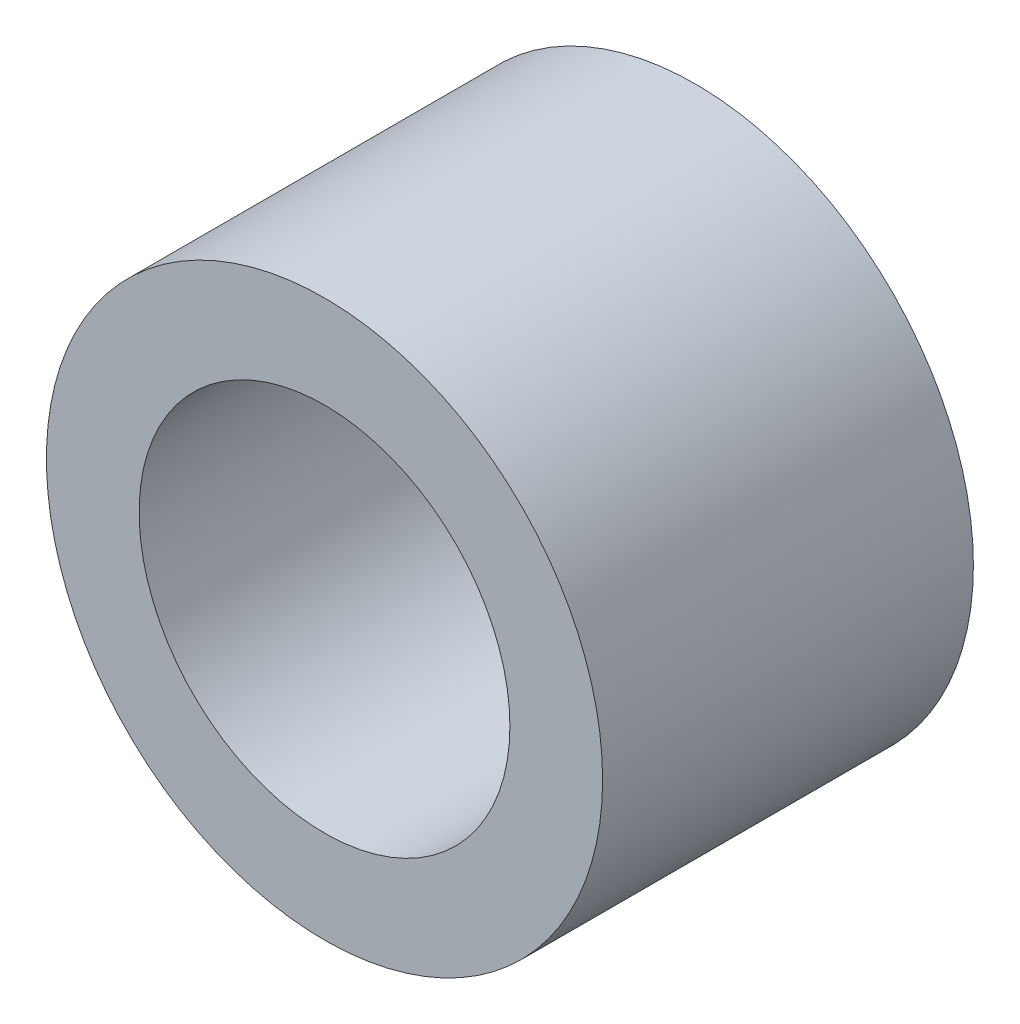
SolidWorks part; units mm, degrees
material "Tin Bearing Bronze"
ref_plane "Front" through (0, 0, 0) normal (0, 0, 1) x (1, 0, 0)
ref_plane "Top" through (0, 0, 0) normal (0, 1, 0) x (1, 0, 0)
ref_plane "Right" through (0, 0, 0) normal (1, 0, 0) x (0, 0, -1)
sketch "Sketch1" plane through (0, 0, 0) normal (0, 0, 1) x (1, 0, 0)
  circle A0 centre (0, 0) radius 6.35
  circle A1 centre (0, 0) radius 9.525
  dimension "D1" = 12.7
  dimension "D2" = 19.05
extrude "Boss-Extrude2" add sketch "Sketch1" along normal blind 12.7
